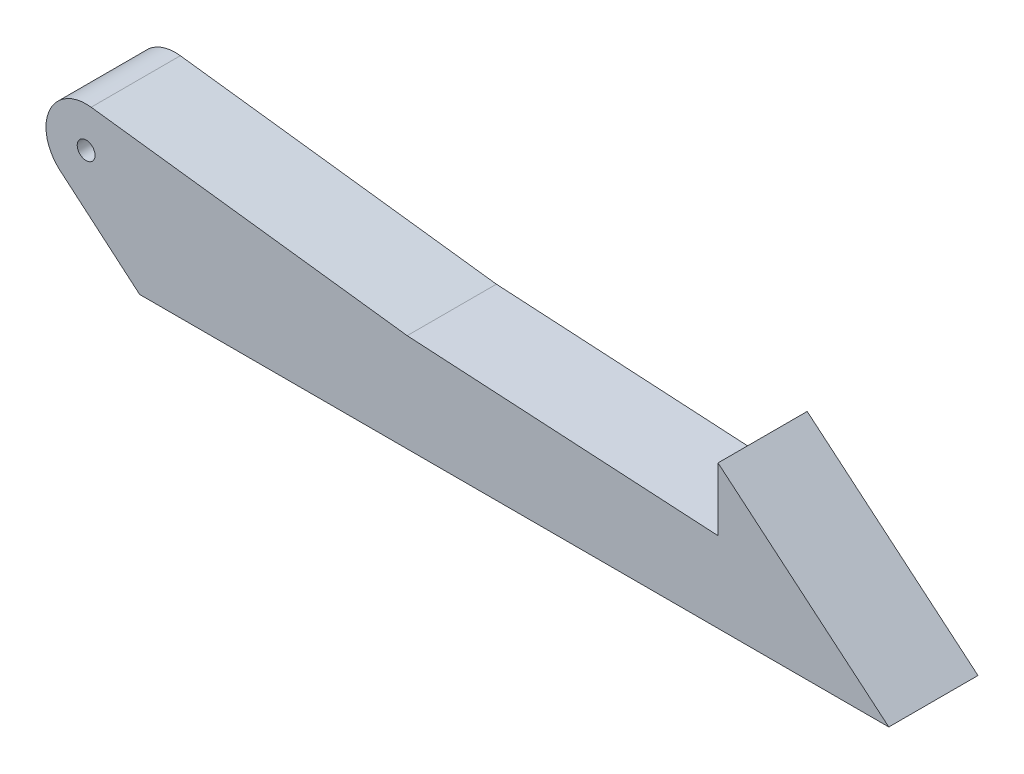
SolidWorks part; units mm, degrees
material "6061-T6 (SS)"
ref_plane "Front Plane" through (0, 0, 0) normal (0, 0, 1) x (1, 0, 0)
ref_plane "Top Plane" through (0, 0, 0) normal (0, 1, 0) x (1, 0, 0)
ref_plane "Right Plane" through (0, 0, 0) normal (1, 0, 0) x (0, 0, -1)
sketch "Sketch3" plane through (0, 0, 0) normal (0, 0, 1) x (1, 0, 0)
  line L0 (0, 0) -> (90, 0) construction
  line L1 (-5, 5) -> (0, 5) construction
  line L2 (-5, 5) -> (-5, -5) construction
  line L3 (-5, -5) -> (0, -5) construction
  line L5 (0.5625, 4.4647) -> (36, 0)
  line L7 (90, -11) -> (70.8489, 5.0697)
  line L10 (0, 0) -> (0, -11) construction
  line L11 (90, -11) -> (6, -11)
  line L12 (6, -11) -> (-2.9131, -3.4299)
  line L13 (36, 0) -> (70.8489, -2)
  line L14 (70.8489, -2) -> (70.8489, 5.0697)
  arc A0 (0.5625, 4.4647) -> (-2.9131, -3.4299) centre (0, 0) ccw
  arc A1 (0, 5) -> (0, -5) centre (0, 0) cw construction
  circle A2 centre (0, 0) radius 1
  point P9 (0, 0)
  point P11 (-5, 0)
  point P14 (0, 0)
  point P15 (0, 0)
  point P16 (0, 0)
  point P18 (70.5464, -1.7058)
  point P19 (0, 0)
  point P21 (30, 0)
  dimension "D3" = 9
  dimension "D4" = 2
  dimension "D1" = 10
  dimension "D2" = 5
  dimension "D5" = 90
  dimension "D6" = 25
  dimension "D7" = 40
  dimension "D8" = 6
  dimension "D9" = 36
  dimension "D10" = 2
  dimension "D11" = 11
extrude "Boss-Extrude1" add sketch "Sketch3" along normal blind 10
